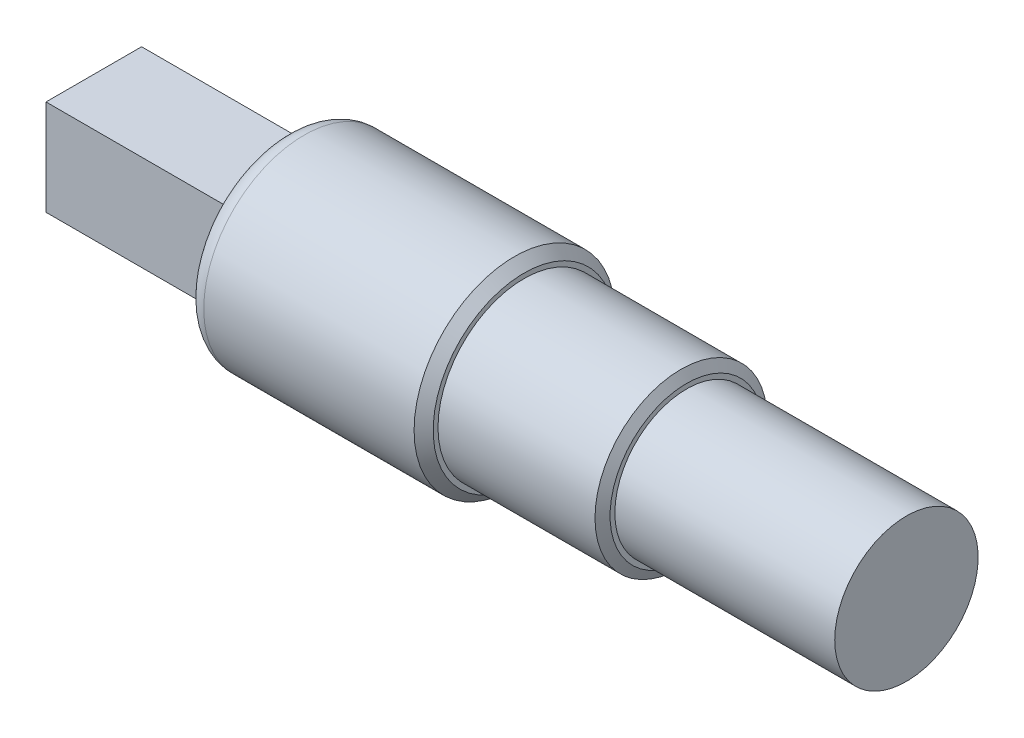
SolidWorks part; units mm, degrees
ref_plane "Спереди" through (0, 0, 0) normal (0, 0, 1) x (1, 0, 0)
ref_plane "Сверху" through (0, 0, 0) normal (0, 1, 0) x (1, 0, 0)
ref_plane "Справа" through (0, 0, 0) normal (1, 0, 0) x (0, 0, -1)
sketch "Эскиз1" plane through (0, 0, 0) normal (0, 0, 1) x (1, 0, 0)
  line L0 (0, 0) -> (20.4783, 0) construction
  line L1 (0, 0) -> (0, -10.5)
  line L2 (0, -10.5) -> (25, -10.5)
  line L3 (25, -10.5) -> (25, -9)
  line L4 (25, -9) -> (42, -9)
  line L5 (42, -9) -> (42, -7.5)
  line L6 (42, -7.5) -> (65, -7.5)
  line L7 (65, -7.5) -> (65, 0)
  line L8 (65, 0) -> (0, 0)
  dimension "D1" = 15
  dimension "D2" = 23
  dimension "D3" = 40
  dimension "D4" = 65
  dimension "D5" = 18
  dimension "D6" = 21
revolve "Повернуть1" add sketch "Эскиз1" angle 360 about L0
sketch "Эскиз2" plane through (0, 0, 0) normal (-1, 0, 0) x (0, 0, 1)
  line L1 (-5, -5) -> (5, -5)
  line L2 (-5, -5) -> (-5, 5)
  line L3 (-5, 5) -> (5, 5)
  line L4 (5, -5) -> (5, 5)
  line L5 (-5, -5) -> (5, 5) construction
  line L6 (-5, 5) -> (5, -5) construction
  point P0 (0, 0)
  point P6 (4.7988, -5.3317)
  dimension "D1" = 10
extrude "Бобышка-Вытянуть1" add sketch "Эскиз2" along normal blind 20
fillet "Скругление1" radius 2 1 edges at (0, 0, 10.5)
chamfer "Фаска1" distance 1 angle 45 1 edges at (25, 0, 10.5)
chamfer "Фаска2" distance 1 angle 30 1 edges at (42, 0, 9)
